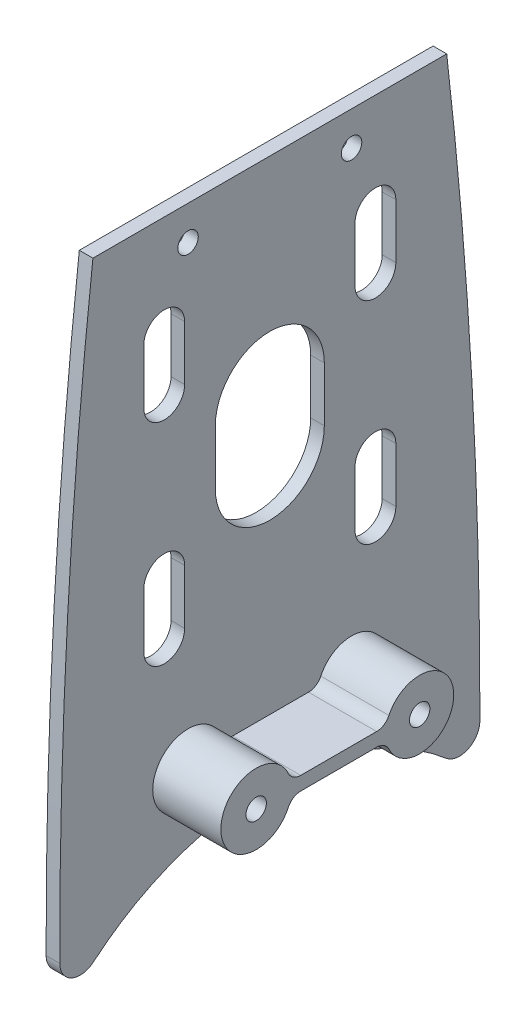
SolidWorks part; units mm, degrees
ref_plane "Front Plane" through (0, 0, 0) normal (0, 0, 1) x (1, 0, 0)
ref_plane "Top Plane" through (0, 0, 0) normal (0, 1, 0) x (1, 0, 0)
ref_plane "Right Plane" through (0, 0, 0) normal (1, 0, 0) x (0, 0, -1)
sketch "Sketch1" plane through (0, 0, 0) normal (1, 0, 0) x (0, 0, -1)
  line L0 (-25.9681, 120) -> (25.9681, 120)
  line L1 (-12, 115) -> (12, 115) construction
  line L2 (-12, 48) -> (12, 48) construction
  line L3 (0, 89.7) -> (0, 81.7) construction
  line L4 (8, 89.7) -> (8, 81.7)
  line L5 (-8, 89.7) -> (-8, 81.7)
  line L6 (15.5, 105.2) -> (15.5, 97.2) construction
  line L7 (18.5, 105.2) -> (18.5, 97.2)
  line L8 (12.5, 105.2) -> (12.5, 97.2)
  line L9 (15.5, 74.2) -> (15.5, 66.2) construction
  line L10 (18.5, 74.2) -> (18.5, 66.2)
  line L11 (12.5, 74.2) -> (12.5, 66.2)
  line L12 (-15.5, 105.2) -> (-15.5, 97.2) construction
  line L13 (-12.5, 105.2) -> (-12.5, 97.2)
  line L14 (-18.5, 105.2) -> (-18.5, 97.2)
  line L15 (-15.5, 74.2) -> (-15.5, 66.2) construction
  line L16 (-12.5, 74.2) -> (-12.5, 66.2)
  line L17 (-18.5, 74.2) -> (-18.5, 66.2)
  line L18 (15.5, 101.2) -> (-15.5, 70.2) construction
  arc A0 (-29.9652, -1.4453) -> (29.9652, -1.4453) centre (0, 0) ccw construction
  arc A1 (-19.7031, 163.4332) -> (19.7031, 163.4332) centre (0, 160) cw construction
  arc A2 (-29.9652, -1.4453) -> (-19.7031, 163.4332) centre (719.1639, 34.6875) cw construction
  arc A3 (29.9652, -1.4453) -> (19.7031, 163.4332) centre (-719.1639, 34.6875) ccw construction
  arc A4 (-25.8917, 30.4896) -> (25.8917, 30.4896) centre (0, 0) cw
  arc A5 (-30.8336, 32.7687) -> (-25.9681, 120) centre (719.1639, 34.6875) cw
  arc A6 (25.9681, 120) -> (30.8336, 32.7687) centre (-719.1639, 34.6875) cw
  circle A7 centre (-12, 115) radius 1.5
  circle A8 centre (12, 115) radius 1.5
  circle A9 centre (-12, 48) radius 1.5
  circle A10 centre (12, 48) radius 1.5
  arc A11 (8, 89.7) -> (-8, 89.7) centre (0, 89.7) ccw
  arc A12 (-8, 81.7) -> (8, 81.7) centre (0, 81.7) ccw
  arc A13 (18.5, 105.2) -> (12.5, 105.2) centre (15.5, 105.2) ccw
  arc A14 (12.5, 97.2) -> (18.5, 97.2) centre (15.5, 97.2) ccw
  arc A15 (18.5, 74.2) -> (12.5, 74.2) centre (15.5, 74.2) ccw
  arc A16 (12.5, 66.2) -> (18.5, 66.2) centre (15.5, 66.2) ccw
  arc A17 (-12.5, 105.2) -> (-18.5, 105.2) centre (-15.5, 105.2) ccw
  arc A18 (-18.5, 97.2) -> (-12.5, 97.2) centre (-15.5, 97.2) ccw
  arc A19 (-12.5, 74.2) -> (-18.5, 74.2) centre (-15.5, 74.2) ccw
  arc A20 (-18.5, 66.2) -> (-12.5, 66.2) centre (-15.5, 66.2) ccw
  arc A21 (25.8917, 30.4896) -> (30.8336, 32.7687) centre (27.8336, 32.7764) ccw
  arc A22 (-25.8917, 30.4896) -> (-30.8336, 32.7687) centre (-27.8336, 32.7764) cw
  point P20 (0, 115)
  point P21 (0, 48)
  point P26 (0, 85.7)
  point P32 (15.5, 101.2)
  point P39 (15.5, 70.2)
  point P46 (-15.5, 101.2)
  point P53 (-15.5, 70.2)
  point P59 (-12.5, 70.2)
  point P62 (0, 85.7)
  dimension "D1" = 30
  dimension "D2" = 20
  dimension "D4" = 750
  dimension "D5" = 750
  dimension "D6" = 40
  dimension "D8" = 3
  dimension "D9" = 3
  dimension "D10" = 3
  dimension "D11" = 3
  dimension "D29" = 3
  dimension "D3" = 160
  dimension "D7" = 40
  dimension "D12" = 24
  dimension "D13" = 24
  dimension "D14" = 45
  dimension "D15" = 48
  dimension "D16" = 8
  dimension "D17" = 16
  dimension "D18" = 74.3
  dimension "D19" = 8
  dimension "D20" = 8
  dimension "D21" = 6
  dimension "D22" = 6
  dimension "D23" = 8
  dimension "D24" = 8
  dimension "D25" = 6
  dimension "D26" = 31
  dimension "D27" = 31
  dimension "D28" = 6
extrude "Boss-Extrude1" add sketch "Sketch1" along normal blind 2
sketch "Sketch2" plane through (2, 0, 0) normal (1, 0, 0) x (0, 0, -1)
  line L0 (-6.9104, 49) -> (7.101, 49)
  line L1 (-6.9104, 47) -> (7.101, 47)
  line L2 (-6.9104, 49) -> (-6.9104, 47) construction
  circle A0 centre (-12, 48) radius 1.5
  circle A1 centre (12, 48) radius 1.5
  arc A2 (-6.9104, 49) -> (-6.9104, 47) centre (-12, 48) ccw
  arc A3 (7.101, 49) -> (7.101, 47) centre (12, 48) cw
  circle A7 centre (12, 48) radius 1.5 construction
  circle A8 centre (-12, 48) radius 1.5 construction
  point P8 (-6.9104, 48)
  dimension "D1" = 5
  dimension "D2" = 5.1869
  dimension "D3" = 2
extrude "Boss-Extrude2" add sketch "Sketch2" along normal blind 10
fillet "Fillet1" radius 2 4 edges at (7, 47, -7.101) (7, 49, -7.101) (7, 49, 6.9104) (7, 47, 6.9104)
